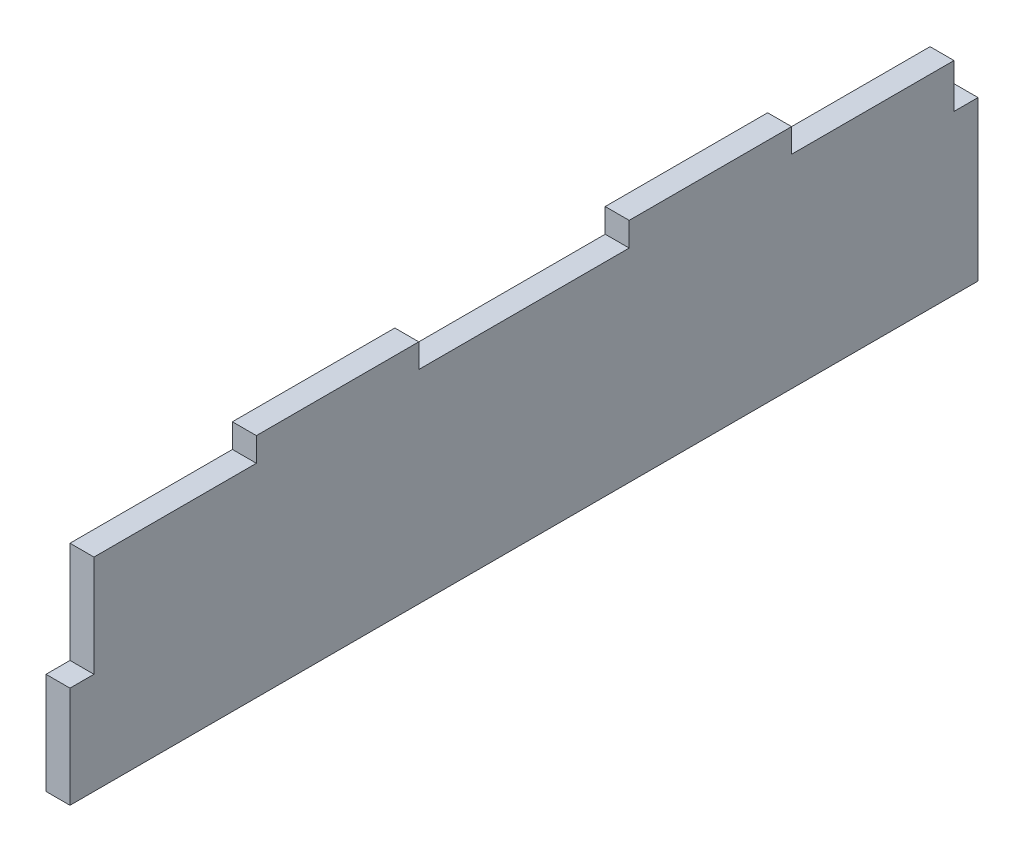
SolidWorks part; units mm, degrees
ref_plane "Alzado" through (0, 0, 0) normal (0, 0, 1) x (1, 0, 0)
ref_plane "Planta" through (0, 0, 0) normal (0, 1, 0) x (1, 0, 0)
ref_plane "Vista lateral" through (0, 0, 0) normal (1, 0, 0) x (0, 0, -1)
sketch "Croquis1" plane through (0, 0, 0) normal (1, 0, 0) x (0, 0, -1)
  line L0 (0, 0) -> (0, 12.7)
  line L1 (0, 12.7) -> (3, 12.7)
  line L2 (3, 12.7) -> (3, 25.4)
  line L3 (3, 25.4) -> (23.32, 25.4)
  line L4 (23.32, 25.4) -> (23.32, 28.4)
  line L5 (23.32, 28.4) -> (43.64, 28.4)
  line L6 (43.64, 28.4) -> (43.64, 25.4)
  line L7 (43.64, 25.4) -> (69.96, 25.4)
  line L8 (69.96, 25.4) -> (69.96, 28.4)
  line L9 (69.96, 28.4) -> (90.28, 28.4)
  line L10 (90.28, 28.4) -> (90.28, 25.4)
  line L11 (90.28, 25.4) -> (110.6, 25.4)
  line L12 (110.6, 25.4) -> (110.6, 19.8867)
  line L13 (110.6, 19.8867) -> (113.6, 19.8867)
  line L14 (113.6, 19.8867) -> (113.6, 0)
  line L15 (113.6, 0) -> (0, 0)
  dimension "D1" = 113.6
  dimension "D2" = 3
  dimension "D3" = 12.7
  dimension "D4" = 12.7
  dimension "D5" = 20.32
  dimension "D6" = 3
  dimension "D7" = 20.32
  dimension "D8" = 20.32
extrude "Saliente-Extruir1" add sketch "Croquis1" along normal blind 3
